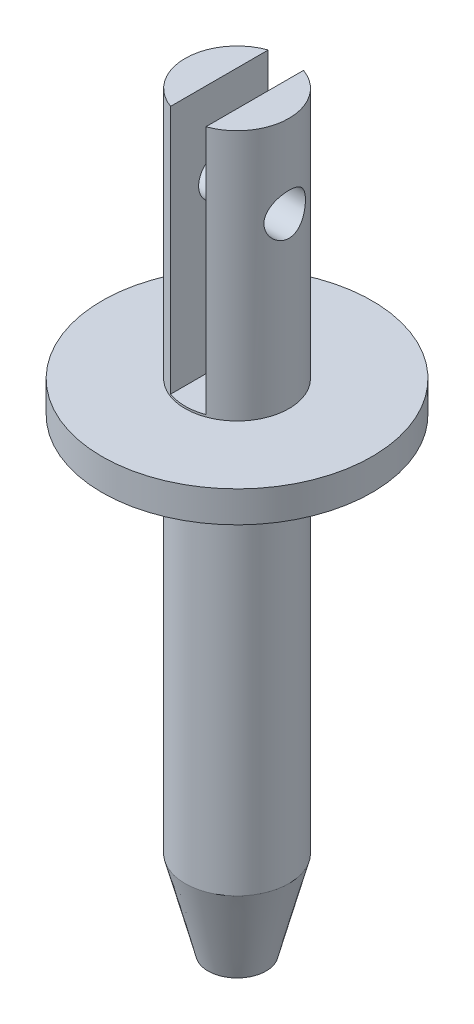
SolidWorks part; units mm, degrees
ref_plane "Front" through (0, 0, 0) normal (0, 0, 1) x (1, 0, 0)
ref_plane "Top" through (0, 0, 0) normal (0, 1, 0) x (1, 0, 0)
ref_plane "Right" through (0, 0, 0) normal (1, 0, 0) x (0, 0, -1)
sketch "Sketch1" plane through (0, 0, 0) normal (0, 1, 0) x (1, 0, 0)
  circle A0 centre (0, 0) radius 2.5
  dimension "D1" = 5
extrude "Boss-Extrude1" add sketch "Sketch1" along normal blind 36.1
sketch "Sketch2" plane through (0, 36.1, 0) normal (0, 1, 0) x (1, 0, 0)
  line L1 (0.85, -3.4091) -> (-0.85, -3.4091)
  line L2 (0.85, -3.4091) -> (0.85, 3.4091)
  line L3 (0.85, 3.4091) -> (-0.85, 3.4091)
  line L4 (-0.85, -3.4091) -> (-0.85, 3.4091)
  line L5 (0.85, -3.4091) -> (-0.85, 3.4091) construction
  line L6 (0.85, 3.4091) -> (-0.85, -3.4091) construction
  point P0 (0, 0)
  dimension "D1" = 1.7
extrude "Cut-Extrude1" cut sketch "Sketch2" against normal blind 12
sketch "Sketch3" plane through (-0.85, 0, 0) normal (1, 0, 0) x (0, 0, -1)
  line L0 (2.3511, 36.1) -> (-2.3511, 36.1) construction
  circle A0 centre (0, 32.1) radius 1
  dimension "D1" = 2
  dimension "D2" = 4
extrude "Cut-Extrude2" cut sketch "Sketch3" against normal mid plane 12
chamfer "Chamfer1" distance 1.1 distance2 4.2 1 edges at (0, 0, 2.5)
ref_axis "Axis1" through (0, 50, 0) along (0, -1, 0)
sketch "Sketch5" plane through (0, 0, 0) normal (1, 0, 0) x (0, 0, -1)
  line L0 (-2.5, 24.1) -> (-2.5, 4.2) construction
  line L1 (-2.5, 23.9974) -> (-6.5, 23.9974)
  line L2 (-2.5, 23.9974) -> (-2.5, 22.4974)
  line L3 (-2.5, 22.4974) -> (-6.5, 22.4974)
  line L4 (-6.5, 23.9974) -> (-6.5, 22.4974)
  dimension "D1" = 1.5
  dimension "D2" = 4
revolve "Revolve1" add sketch "Sketch5" angle 360 about axis through (0, 50, 0) along (0, -1, 0)
